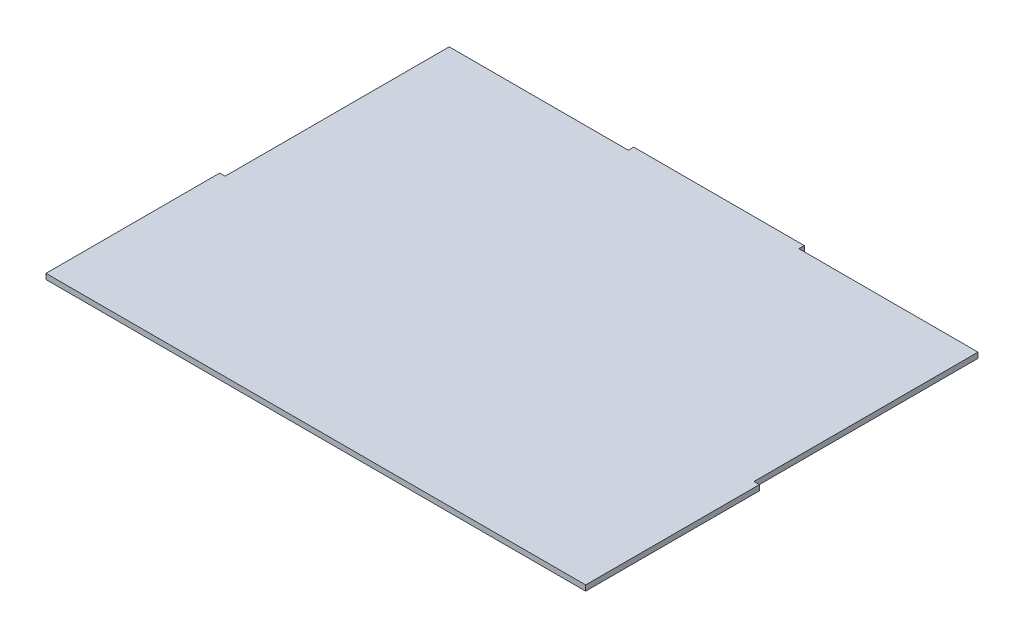
SolidWorks part; units mm, degrees
material "6061-T6 (SS)"
ref_plane "X-Y Datum" through (0, 0, 0) normal (0, 0, 1) x (1, 0, 0)
ref_plane "X-Z Datum" through (0, 0, 0) normal (0, 1, 0) x (1, 0, 0)
ref_plane "Y-Z Datum" through (0, 0, 0) normal (1, 0, 0) x (0, 0, -1)
sketch "Sketch1" plane through (0, 0, 0) normal (0, 0, 1) x (1, 0, 0)
  line L1 (-157.79, -1.5875) -> (157.79, -1.5875)
  line L2 (-157.79, -1.5875) -> (-157.79, 1.5875)
  line L3 (-157.79, 1.5875) -> (157.79, 1.5875)
  line L4 (157.79, -1.5875) -> (157.79, 1.5875)
  line L5 (-157.79, -1.5875) -> (157.79, 1.5875) construction
  line L6 (-157.79, 1.5875) -> (157.79, -1.5875) construction
  point P0 (0, 0)
  dimension "D1" = 315.58
  dimension "D2" = 3.175
extrude "Boss-Extrude1" add sketch "Sketch1" along normal blind 232.6
sketch "Sketch5" plane through (0, 1.5875, 0) normal (0, 1, 0) x (1, 0, 0)
  line L15 (-157.79, 0) -> (-154.615, 0)
  line L16 (-157.79, 0) -> (-157.79, -131)
  line L17 (-157.79, -131) -> (-154.615, -131)
  line L18 (-154.615, 0) -> (-154.615, -131)
  dimension "D3" = 3.175
  dimension "D4" = 131
extrude "Cut-Extrude2" cut sketch "Sketch5" against normal through all and the other way through all
mirror "Mirror1" about plane through (0, 0, 0) normal (1, 0, 0) of "Cut-Extrude2"
sketch "Sketch7" plane through (0, -1.5875, 0) normal (0, -1, 0) x (1, 0, 0)
  line L0 (110.4954, 221.3083) -> (104.4954, 221.3083) construction
  circle A0 centre (107.4954, 221.3083) radius 3.302
  dimension "D1" = 6.604
extrude "Cut-Extrude3" [suppressed] cut sketch "Sketch7" against normal through all
pattern_linear "LPattern1" [suppressed] count 3 spacing 101.6
sketch "Sketch8" plane through (0, 0, 0) normal (0, 0, -1) x (-1, 0, 0)
  line L0 (-154.615, -1.5875) -> (-154.615, 1.5875) construction
  line L4 (-154.615, 1.5875) -> (154.615, 1.5875) construction
  line L5 (49.84, 1.5875) -> (-49.84, 1.5875)
  line L6 (49.84, 1.5875) -> (49.84, -1.5875)
  line L7 (49.84, -1.5875) -> (-49.84, -1.5875)
  line L8 (-49.84, 1.5875) -> (-49.84, -1.5875)
  line L9 (154.615, -1.5875) -> (-154.615, -1.5875) construction
  dimension "D1" = 104.775
extrude "Boss-Extrude2" add sketch "Sketch8" along normal blind 3.175
